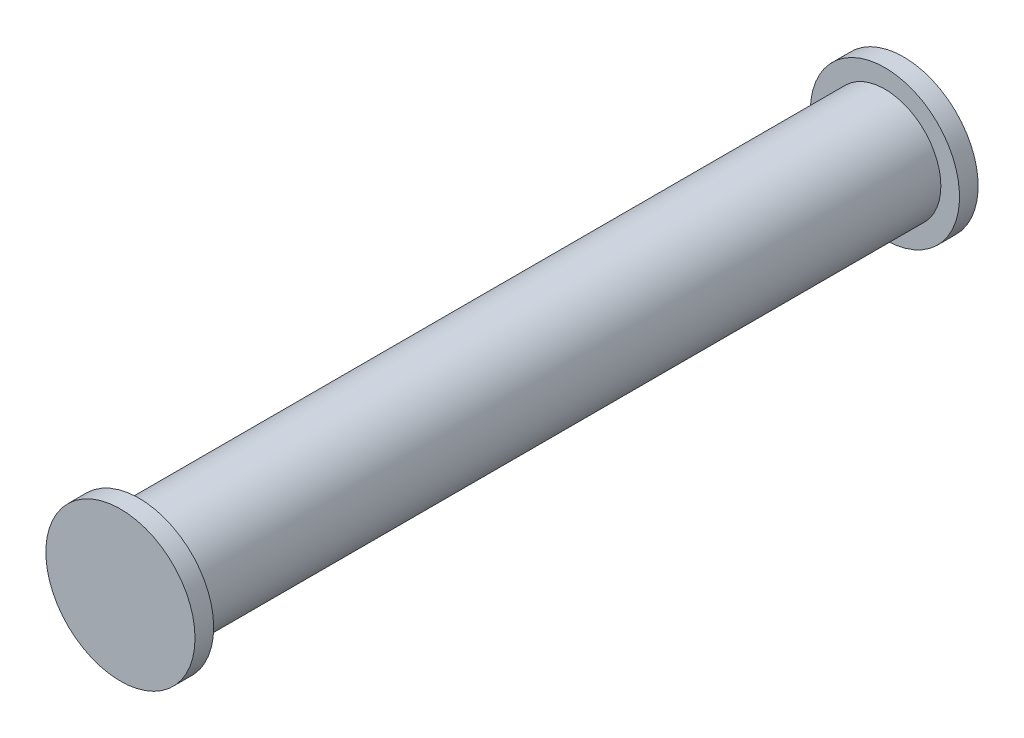
SolidWorks part; units mm, degrees
ref_plane "Front Plane" through (0, 0, 0) normal (0, 0, 1) x (1, 0, 0)
ref_plane "Top Plane" through (0, 0, 0) normal (0, 1, 0) x (1, 0, 0)
ref_plane "Right Plane" through (0, 0, 0) normal (1, 0, 0) x (0, 0, -1)
sketch "Sketch1" plane through (0, 0, 0) normal (0, 0, 1) x (1, 0, 0)
  circle A0 centre (0, 0) radius 19.05
  dimension "D1" = 38.1
extrude "Boss-Extrude1" add sketch "Sketch1" along normal blind 254
sketch "Sketch2" plane through (0, 0, 254) normal (0, 0, 1) x (1, 0, 0)
  circle A0 centre (0, 0) radius 25.4
  dimension "D1" = 50.8
extrude "Boss-Extrude2" add sketch "Sketch2" along normal blind 6.35
sketch "Sketch3" plane through (0, 0, 0) normal (0, 0, -1) x (-1, 0, 0)
  circle A0 centre (0, 0) radius 25.4
  dimension "D1" = 50.8
extrude "Boss-Extrude3" add sketch "Sketch3" along normal blind 6.35
